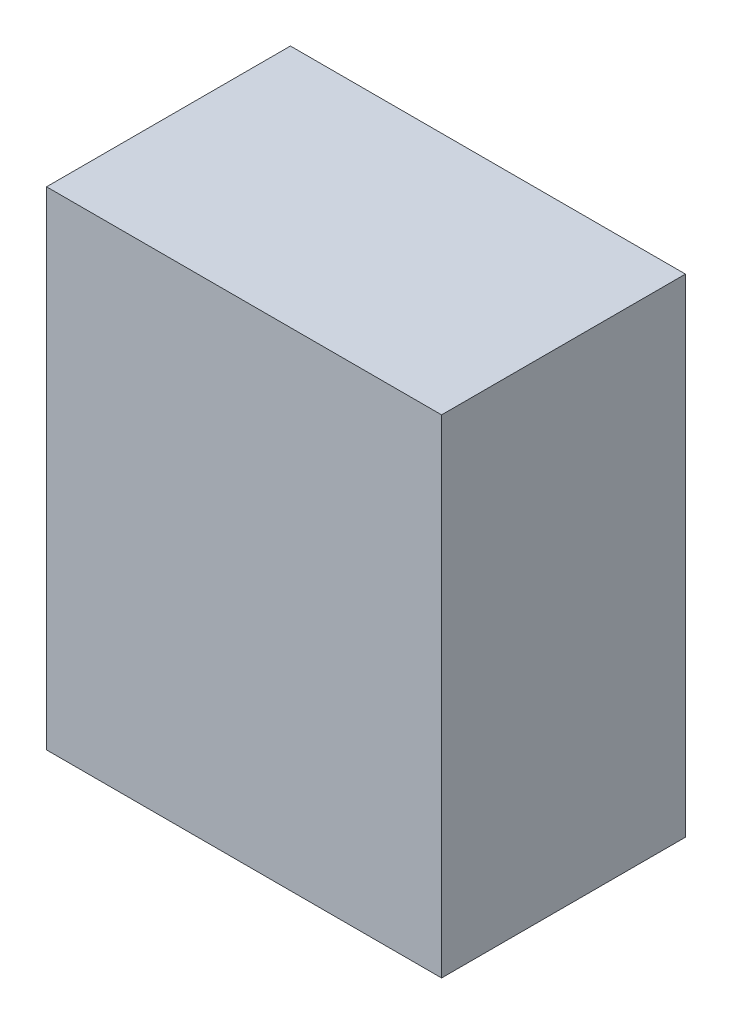
SolidWorks part; units mm, degrees
ref_plane "Front Plane" through (0, 0, 0) normal (0, 0, 1) x (1, 0, 0)
ref_plane "Top Plane" through (0, 0, 0) normal (0, 1, 0) x (1, 0, 0)
ref_plane "Right Plane" through (0, 0, 0) normal (1, 0, 0) x (0, 0, -1)
sketch "Sketch1" plane through (0, 0, 0) normal (0, 0, 1) x (1, 0, 0)
  line L1 (0, 0) -> (16.2, 0)
  line L2 (0, 0) -> (0, 20)
  line L3 (0, 20) -> (16.2, 20)
  line L4 (16.2, 0) -> (16.2, 20)
extrude "Boss-Extrude1" add sketch "Sketch1" along normal blind 10
